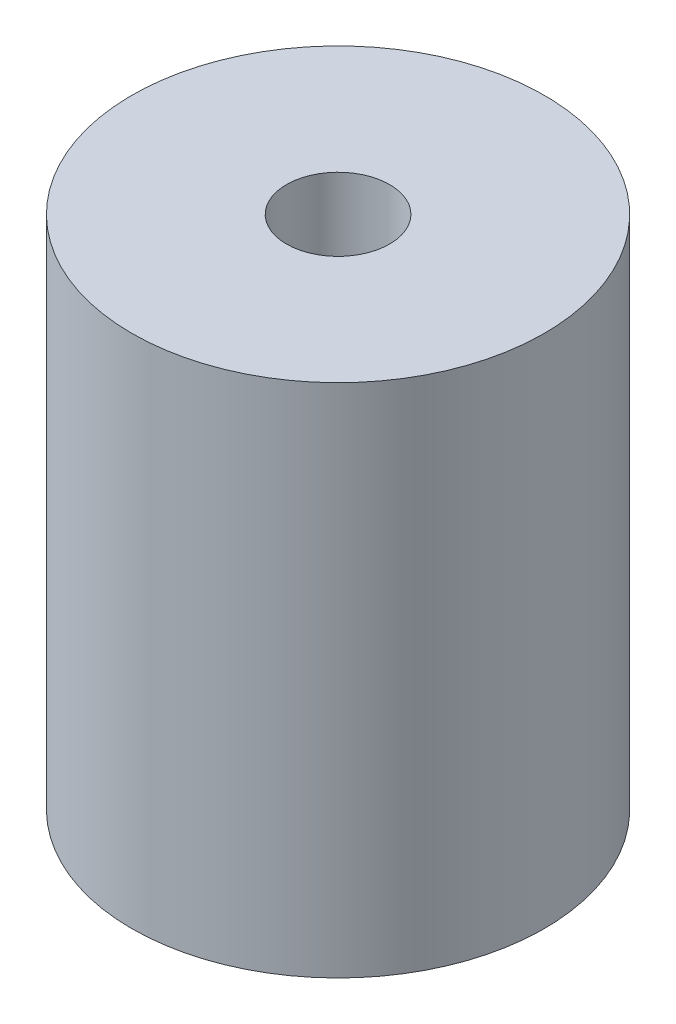
SolidWorks part; units mm, degrees
ref_plane "前视基准面" through (0, 0, 0) normal (0, 0, 1) x (1, 0, 0)
ref_plane "上视基准面" through (0, 0, 0) normal (0, 1, 0) x (1, 0, 0)
ref_plane "右视基准面" through (0, 0, 0) normal (1, 0, 0) x (0, 0, -1)
sketch "草图1" plane through (0, 0, 0) normal (0, 1, 0) x (1, 0, 0)
  circle A0 centre (0, 0) radius 2.5
  circle A1 centre (0, 0) radius 10
  dimension "D1" = 5
  dimension "D2" = 20
extrude "凸台-拉伸1" add sketch "草图1" along normal blind 25
